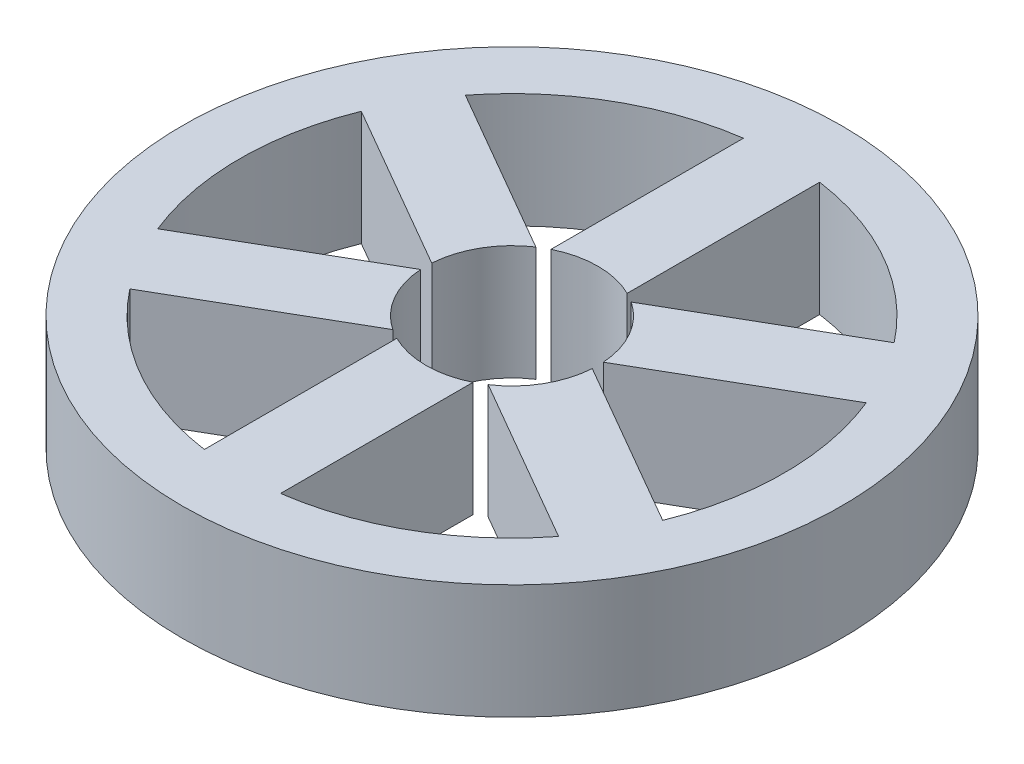
SolidWorks part; units mm, degrees
ref_plane "Front Plane" through (0, 0, 0) normal (0, 0, 1) x (1, 0, 0)
ref_plane "Top Plane" through (0, 0, 0) normal (0, 1, 0) x (1, 0, 0)
ref_plane "Right Plane" through (0, 0, 0) normal (1, 0, 0) x (0, 0, -1)
sketch "Sketch1" plane through (0, 0, 0) normal (0, 1, 0) x (1, 0, 0)
  line L6 (0.8322, -1.248) -> (3.7408, -2.9272)
  line L8 (-0.6647, -1.3447) -> (-0.6647, -4.7033)
  line L9 (-0.8322, -1.248) -> (-3.7408, -2.9272)
  line L11 (-0.3323, -0.5756) -> (-0.6647, -0.3837)
  line L13 (0.6647, 1.3447) -> (0.6647, 4.7033)
  line L14 (0.8322, 1.248) -> (3.7408, 2.9272)
  line L16 (-0.8322, 1.248) -> (-3.7408, 2.9272)
  line L17 (-0.6647, 1.3447) -> (-0.6647, 4.7033)
  line L18 (-1.4969, -0.0967) -> (-4.4055, -1.776)
  line L19 (0.6647, -1.3447) -> (0.6647, -4.7033)
  line L20 (1.4969, 0.0967) -> (4.4055, 1.776)
  line L21 (1.4969, -0.0967) -> (4.4055, -1.776)
  line L26 (-1.4969, 0.0967) -> (-4.4055, 1.776)
  circle A0 centre (0, 0) radius 5.75
  arc A1 (-4.4055, 1.776) -> (-4.4055, -1.776) centre (0, 0) ccw
  circle A2 centre (0, 0) radius 1.5
  arc A3 (-0.6647, 4.7033) -> (-3.7408, 2.9272) centre (0, 0) ccw
  arc A4 (3.7408, 2.9272) -> (0.6647, 4.7033) centre (0, 0) ccw
  arc A5 (4.4055, -1.776) -> (4.4055, 1.776) centre (0, 0) ccw
  arc A6 (0.6647, -4.7033) -> (3.7408, -2.9272) centre (0, 0) ccw
  arc A7 (-3.7408, -2.9272) -> (-0.6647, -4.7033) centre (0, 0) ccw
  point P32 (0, 0)
  dimension "D1" = 11.5
  dimension "D2" = 9.5
  dimension "D3" = 3
extrude "Boss-Extrude1" add sketch "Sketch1" along normal blind 2 contours A0 A7 L9 A2 L18 A1 L26 L16 A3 L17 L13 A4 L14 L20 A5 L21 L6 A6 L19 L8
